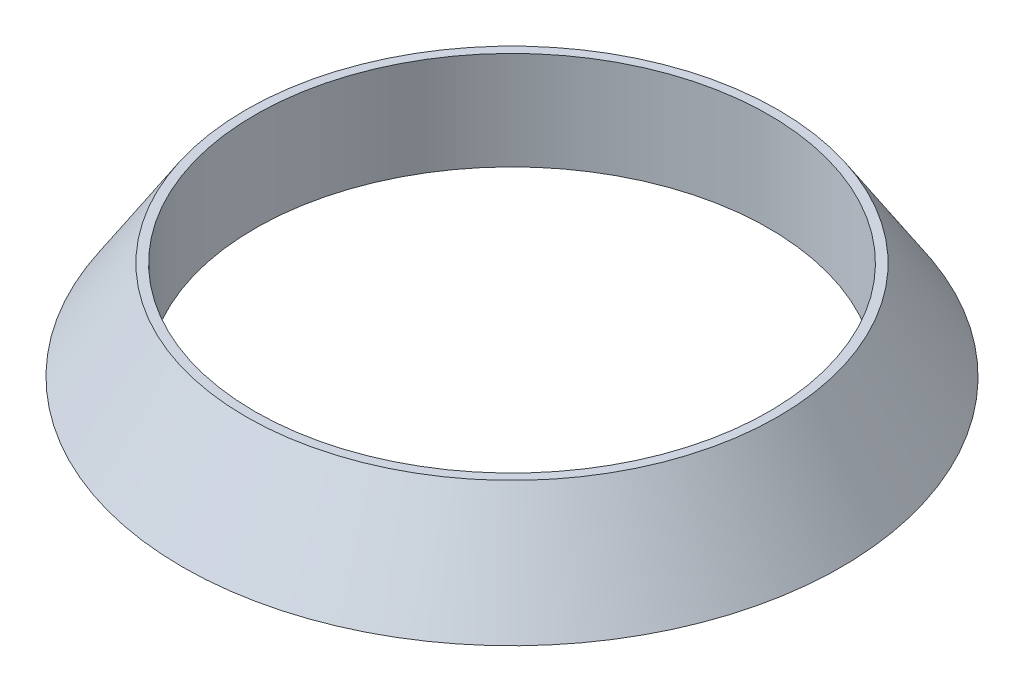
SolidWorks part; units mm, degrees
ref_plane "Front Plane" through (0, 0, 0) normal (0, 0, 1) x (1, 0, 0)
ref_plane "Top Plane" through (0, 0, 0) normal (0, 1, 0) x (1, 0, 0)
ref_plane "Right Plane" through (0, 0, 0) normal (1, 0, 0) x (0, 0, -1)
sketch "Sketch2" plane through (0, 0, 0) normal (0, 1, 0) x (1, 0, 0)
  circle A0 centre (0, 0) radius 85.1665
  circle A1 centre (0, 0) radius 66.4163
extrude "Boss-Extrude1" add sketch "Sketch2" along normal blind 25.4
sketch "Sketch5" plane through (0, 0, 0) normal (1, 0, 0) x (0, 0, -1)
  line L0 (-85.1665, 0) -> (-68.7323, 25.4)
  line L1 (85.1665, 25.4) -> (-85.1665, 25.4) construction
  line L2 (-68.7323, 25.4) -> (-85.1665, 25.4)
  line L3 (-85.1665, 25.4) -> (-85.1665, 0)
  line L4 (0, 0) -> (0, 50000) construction
revolve "Cut-Revolve2" cut sketch "Sketch5" angle 360 about L4
